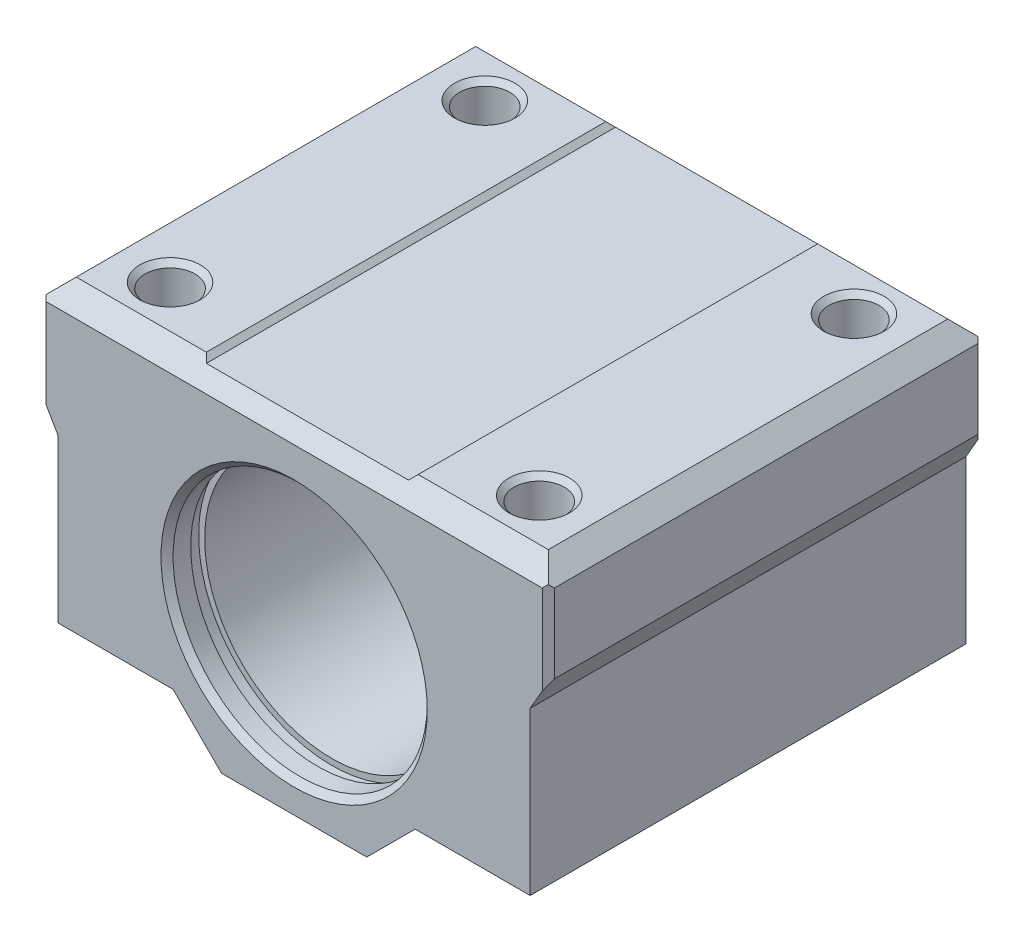
SolidWorks part; units mm, degrees
material "2014 Alloy"
ref_plane "Front Plane" through (0, 0, 0) normal (0, 0, 1) x (1, 0, 0)
ref_plane "Top Plane" through (0, 0, 0) normal (0, 1, 0) x (1, 0, 0)
ref_plane "Right Plane" through (0, 0, 0) normal (1, 0, 0) x (0, 0, -1)
ref_plane "Plane1" through (0, 0, 0) normal (0, 0, 1) x (1, 0, 0)
sketch "Sketch1" plane through (0, 0, 0) normal (0, 0, 1) x (1, 0, 0)
  line L0 (-21, 13.5) -> (-21, 7)
  line L1 (-21, 7) -> (-19.5, 4.4019)
  line L2 (-19.5, 4.4019) -> (-19.5, -9)
  line L3 (-19.5, -9) -> (-10, -9)
  line L4 (-10, -9) -> (-6, -13)
  line L5 (-6, -13) -> (6, -13)
  line L6 (6, -13) -> (10, -9)
  line L7 (10, -9) -> (19.5, -9)
  line L8 (19.5, -9) -> (19.5, 4.4019)
  line L9 (19.5, 4.4019) -> (21, 7)
  line L10 (21, 7) -> (21, 13.5)
  line L11 (21, 13.5) -> (19.5, 15)
  line L12 (19.5, 15) -> (8.75, 15)
  line L13 (8.75, 15) -> (8.35, 14.6)
  line L14 (8.35, 14.6) -> (-8.35, 14.6)
  line L15 (-8.35, 14.6) -> (-8.75, 15)
  line L16 (-8.75, 15) -> (-19.5, 15)
  line L17 (-19.5, 15) -> (-21, 13.5)
extrude "Boss-Extrude1" add sketch "Sketch1" along normal blind 36
ref_plane "Plane2" through (0, 0, 0) normal (1, 0, 0) x (0, 0, -1)
sketch "Sketch2" plane through (0, 0, 0) normal (1, 0, 0) x (0, 0, -1)
  line L0 (-45, 28) -> (-45, -28)
  line L1 (-45, -28) -> (9, -28)
  line L2 (9, -28) -> (9, 28)
  line L3 (9, 28) -> (-45, 28)
  line L4 (-36, 13.5) -> (-36, -13)
  line L5 (-36, -13) -> (0, -13)
  line L6 (0, -13) -> (0, 13.5)
  line L7 (0, 13.5) -> (-1.5, 15)
  line L8 (-1.5, 15) -> (-34.5, 15)
  line L9 (-34.5, 15) -> (-36, 13.5)
extrude "Cut-Extrude1" cut sketch "Sketch2" against normal blind 21 and the other way blind 21
ref_plane "Plane3" through (0, 0, 0) normal (1, 0, 0) x (0, 0, -1)
sketch "Sketch3" plane through (0, 0, 0) normal (1, 0, 0) x (0, 0, -1)
  line L0 (-36, 0) -> (-36, 11)
  line L1 (-36, 11) -> (-35.5, 10.5)
  line L2 (-35.5, 10.5) -> (-34.04, 10.5)
  line L3 (-34.04, 10.5) -> (-34.04, 11)
  line L4 (-34.04, 11) -> (-32.89, 11)
  line L5 (-32.89, 11) -> (-32.89, 10.5)
  line L6 (-32.89, 10.5) -> (-3.11, 10.5)
  line L7 (-3.11, 10.5) -> (-3.11, 11)
  line L8 (-3.11, 11) -> (-1.96, 11)
  line L9 (-1.96, 11) -> (-1.96, 10.5)
  line L10 (-1.96, 10.5) -> (-0.5, 10.5)
  line L11 (-0.5, 10.5) -> (0, 11)
  line L12 (0, 11) -> (0, 0)
  line L13 (0, 0) -> (-36, 0)
  line L14 (0, 0) -> (-36, 0) construction
revolve "Cut-Revolve1" cut sketch "Sketch3" angle 360 about L14
ref_plane "Plane4" through (0, 0, 0) normal (0, 1, 0) x (1, 0, 0)
sketch "Sketch4" plane through (0, 0, 0) normal (0, 1, 0) x (1, 0, 0)
  line L0 (-26, -41) -> (26, -41)
  line L1 (26, -41) -> (26, 5)
  line L2 (26, 5) -> (-26, 5)
  line L3 (-26, 5) -> (-26, -41)
  line L4 (-21, -0.5) -> (-21, -35.5)
  line L5 (-21, -35.5) -> (-20.5, -36)
  line L6 (-20.5, -36) -> (20.5, -36)
  line L7 (20.5, -36) -> (21, -35.5)
  line L8 (21, -35.5) -> (21, -0.5)
  line L9 (21, -0.5) -> (20.5, 0)
  line L10 (20.5, 0) -> (-20.5, 0)
  line L11 (-20.5, 0) -> (-21, -0.5)
extrude "Cut-Extrude2" cut sketch "Sketch4" against normal blind 28 and the other way blind 28
ref_plane "Plane5" through (15.25, 0, 0) normal (1, 0, 0) x (0, 0, -1)
sketch "Sketch5" plane through (15.25, 0, 0) normal (1, 0, 0) x (0, 0, -1)
  line L0 (-5, 15) -> (-2.5, 15)
  line L1 (-2.5, 15) -> (-2.933, 14.567)
  line L2 (-2.933, 14.567) -> (-2.933, 1)
  line L3 (-2.933, 1) -> (-2.85, 1)
  line L4 (-2.85, 1) -> (-2.85, -8.6)
  line L5 (-2.85, -8.6) -> (-2.6191, -9)
  line L6 (-2.6191, -9) -> (-5, -9)
  line L7 (-5, -9) -> (-5, 15)
  line L8 (-5, -9) -> (-5, 15) construction
revolve "Cut-Revolve2" cut sketch "Sketch5" angle 360 about L8
cosmetic thread "Cosmetic Thread1" parameters "D1"=12, "D2"=5
ref_plane "Plane6" through (15.25, 0, 0) normal (1, 0, 0) x (0, 0, -1)
sketch "Sketch6" plane through (15.25, 0, 0) normal (1, 0, 0) x (0, 0, -1)
  line L0 (-31, 15) -> (-28.5, 15)
  line L1 (-28.5, 15) -> (-28.933, 14.567)
  line L2 (-28.933, 14.567) -> (-28.933, 1)
  line L3 (-28.933, 1) -> (-28.85, 1)
  line L4 (-28.85, 1) -> (-28.85, -8.6)
  line L5 (-28.85, -8.6) -> (-28.6191, -9)
  line L6 (-28.6191, -9) -> (-31, -9)
  line L7 (-31, -9) -> (-31, 15)
  line L8 (-31, -9) -> (-31, 15) construction
revolve "Cut-Revolve3" cut sketch "Sketch6" angle 360 about L8
cosmetic thread "Cosmetic Thread2" parameters "D1"=12, "D2"=5
ref_plane "Plane7" through (-15.25, 0, 0) normal (1, 0, 0) x (0, 0, -1)
sketch "Sketch7" plane through (-15.25, 0, 0) normal (1, 0, 0) x (0, 0, -1)
  line L0 (-5, 15) -> (-2.5, 15)
  line L1 (-2.5, 15) -> (-2.933, 14.567)
  line L2 (-2.933, 14.567) -> (-2.933, 1)
  line L3 (-2.933, 1) -> (-2.85, 1)
  line L4 (-2.85, 1) -> (-2.85, -8.6)
  line L5 (-2.85, -8.6) -> (-2.6191, -9)
  line L6 (-2.6191, -9) -> (-5, -9)
  line L7 (-5, -9) -> (-5, 15)
  line L8 (-5, -9) -> (-5, 15) construction
revolve "Cut-Revolve4" cut sketch "Sketch7" angle 360 about L8
cosmetic thread "Cosmetic Thread3" parameters "D1"=12, "D2"=5
ref_plane "Plane8" through (-15.25, 0, 0) normal (1, 0, 0) x (0, 0, -1)
sketch "Sketch8" plane through (-15.25, 0, 0) normal (1, 0, 0) x (0, 0, -1)
  line L0 (-31, 15) -> (-28.5, 15)
  line L1 (-28.5, 15) -> (-28.933, 14.567)
  line L2 (-28.933, 14.567) -> (-28.933, 1)
  line L3 (-28.933, 1) -> (-28.85, 1)
  line L4 (-28.85, 1) -> (-28.85, -8.6)
  line L5 (-28.85, -8.6) -> (-28.6191, -9)
  line L6 (-28.6191, -9) -> (-31, -9)
  line L7 (-31, -9) -> (-31, 15)
  line L8 (-31, -9) -> (-31, 15) construction
revolve "Cut-Revolve5" cut sketch "Sketch8" angle 360 about L8
cosmetic thread "Cosmetic Thread4" parameters "D1"=12, "D2"=5
